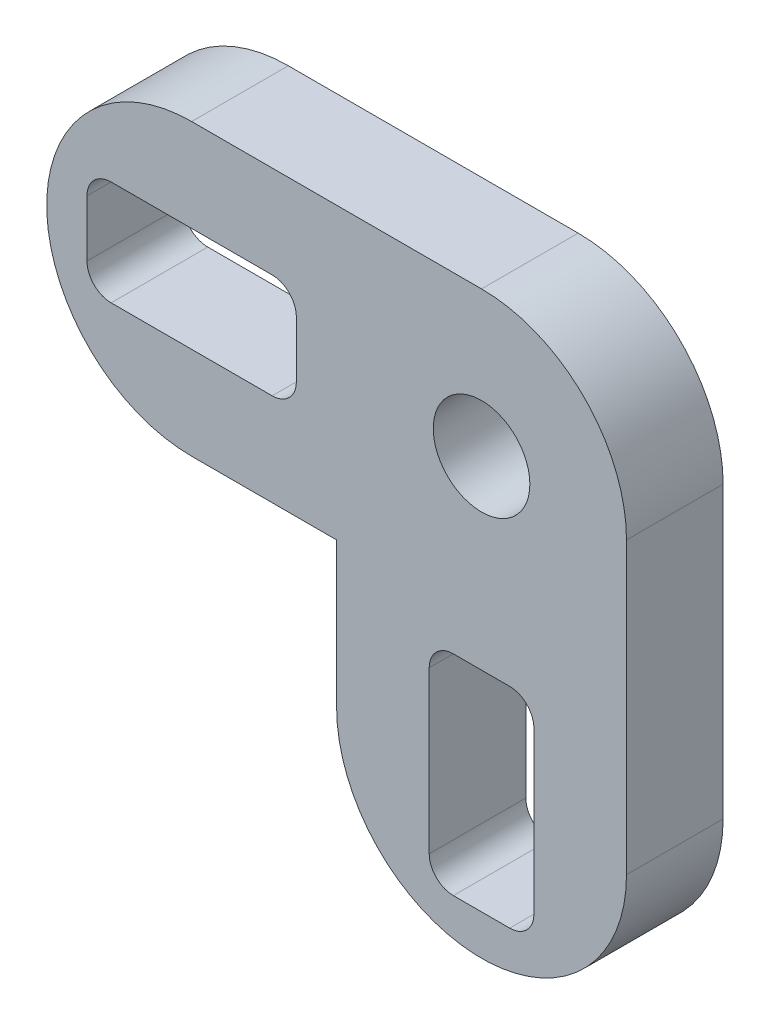
SolidWorks part; units mm, degrees
ref_plane "Alzado" through (0, 0, 0) normal (0, 0, 1) x (1, 0, 0)
ref_plane "Planta" through (0, 0, 0) normal (0, 1, 0) x (1, 0, 0)
ref_plane "Vista lateral" through (0, 0, 0) normal (1, 0, 0) x (0, 0, -1)
sketch "Model" plane through (0, 0, 0) normal (0, 0, 1) x (1, 0, 0)
  line L0 (149.3421, 211.824) -> (158.3421, 211.824)
  line L1 (153.8421, 202.824) -> (149.3421, 202.824)
  line L2 (162.8421, 198.324) -> (162.8421, 207.324)
  line L3 (153.8421, 198.324) -> (153.8421, 202.824)
  line L4 (156.7171, 195.824) -> (156.7171, 200.824)
  line L5 (157.4671, 201.574) -> (159.2171, 201.574)
  line L6 (159.9671, 200.824) -> (159.9671, 195.824)
  line L7 (159.2171, 195.074) -> (157.4671, 195.074)
  line L8 (151.8421, 205.699) -> (146.8421, 205.699)
  line L9 (146.0921, 206.449) -> (146.0921, 208.199)
  line L10 (146.8421, 208.949) -> (151.8421, 208.949)
  line L11 (152.5921, 208.199) -> (152.5921, 206.449)
  arc A0 (149.3421, 211.824) -> (149.3421, 202.824) centre (149.3421, 207.324) ccw
  arc A1 (162.8421, 207.324) -> (158.3421, 211.824) centre (158.3421, 207.324) ccw
  circle A2 centre (158.3421, 207.324) radius 1.5
  arc A3 (153.8421, 198.324) -> (162.8421, 198.324) centre (158.3421, 198.324) ccw
  arc A4 (157.4671, 201.574) -> (156.7171, 200.824) centre (157.4671, 200.824) ccw
  arc A5 (159.9671, 200.824) -> (159.2171, 201.574) centre (159.2171, 200.824) ccw
  arc A6 (159.2171, 195.074) -> (159.9671, 195.824) centre (159.2171, 195.824) ccw
  arc A7 (156.7171, 195.824) -> (157.4671, 195.074) centre (157.4671, 195.824) ccw
  arc A8 (146.0921, 206.449) -> (146.8421, 205.699) centre (146.8421, 206.449) ccw
  arc A9 (146.8421, 208.949) -> (146.0921, 208.199) centre (146.8421, 208.199) ccw
  arc A10 (152.5921, 208.199) -> (151.8421, 208.949) centre (151.8421, 208.199) ccw
  arc A11 (151.8421, 205.699) -> (152.5921, 206.449) centre (151.8421, 206.449) ccw
extrude "Saliente-Extruir1" add sketch "Model" along normal blind 3
